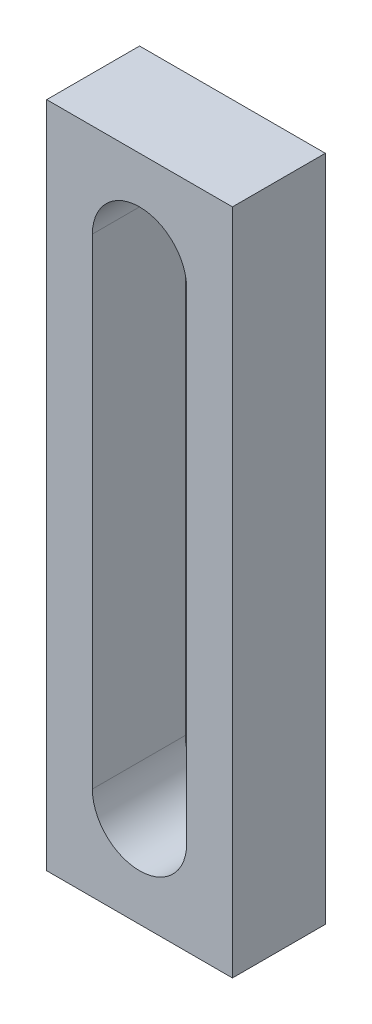
SolidWorks part; units mm, degrees
ref_plane "Front Plane" through (0, 0, 0) normal (0, 0, 1) x (1, 0, 0)
ref_plane "Top Plane" through (0, 0, 0) normal (0, 1, 0) x (1, 0, 0)
ref_plane "Right Plane" through (0, 0, 0) normal (1, 0, 0) x (0, 0, -1)
sketch "Sketch1" plane through (0, 0, 0) normal (0, 0, 1) x (1, 0, 0)
  line L0 (0, 91.315) -> (0, -91.315)
  line L1 (0, -91.315) -> (50.8, -91.315)
  line L2 (50.8, -91.315) -> (50.8, 91.315)
  line L3 (50.8, 91.315) -> (0, 91.315)
  point P5 (50.8, 70.536)
  point P6 (0, 0)
  dimension "D1" = 182.63
  dimension "D2" = 50.8
extrude "Boss-Extrude1" add sketch "Sketch1" along normal blind 25.4 contours L3 L0 L1 L2
sketch "Sketch2" plane through (0, 0, 25.4) normal (0, 0, 1) x (1, 0, 0)
  line L0 (25.4, 65.715) -> (25.4, -65.715) construction
  line L1 (38.3, 65.715) -> (38.3, -65.715)
  line L2 (12.5, 65.715) -> (12.5, -65.715)
  line L4 (50.8, 91.315) -> (0, 91.315) construction
  arc A0 (38.3, 65.715) -> (12.5, 65.715) centre (25.4, 65.715) ccw
  arc A1 (12.5, -65.715) -> (38.3, -65.715) centre (25.4, -65.715) ccw
  point P2 (25.4, 0)
  point P7 (0, 0)
  point P10 (25.4, 91.315)
  point P11 (25.4, 78.615)
  dimension "D1" = 12.7
  dimension "D2" = 25.8
extrude "Cut-Extrude1" cut sketch "Sketch2" against normal through all both and the other way through all contours L2 A1 L1 A0
